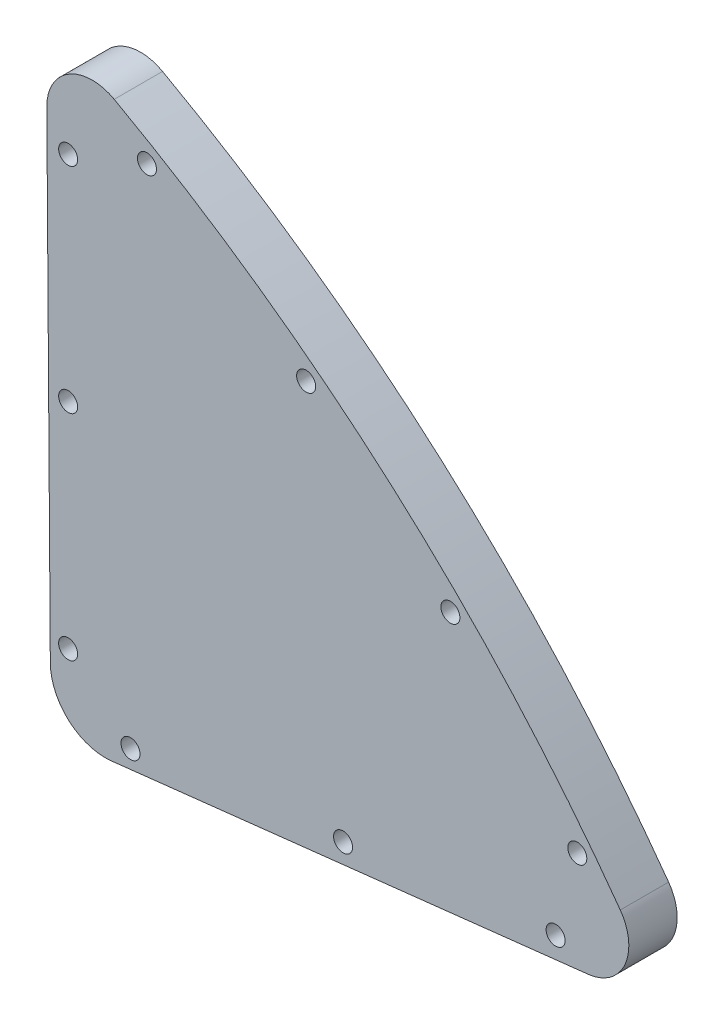
SolidWorks part; units mm, degrees
ref_plane "Front Plane" through (0, 0, 0) normal (0, 0, 1) x (1, 0, 0)
ref_plane "Top Plane" through (0, 0, 0) normal (0, 1, 0) x (1, 0, 0)
ref_plane "Right Plane" through (0, 0, 0) normal (1, 0, 0) x (0, 0, -1)
sketch "Sketch1" plane through (0, 0, 0) normal (0, 0, 1) x (1, 0, 0)
  line L27 (0.9289, -25.6035) -> (126.2631, -11.5065)
  line L28 (-16.0858, 114.7994) -> (-15.167, -11.3217)
  line L29 (0.9289, -25.6035) -> (126.2631, -11.5065)
  line L30 (-16.0858, 114.7994) -> (-15.167, -11.3217)
  arc A47 (-15.167, -11.3217) -> (0.9289, -25.6035) centre (-0.6893, -11.2163) ccw
  arc A48 (126.2631, -11.5065) -> (134.6163, 7.3328) centre (124.9288, 0.3567) ccw
  arc A49 (134.6163, 7.3328) -> (1.6255, 125.3353) centre (-194.5558, -229.707) ccw
  arc A50 (1.6255, 125.3353) -> (-16.0858, 114.7994) centre (-4.1481, 114.8864) ccw
  arc A51 (-15.167, -11.3217) -> (0.9289, -25.6035) centre (-0.6893, -11.2163) ccw
  arc A52 (126.2631, -11.5065) -> (134.6163, 7.3328) centre (124.9288, 0.3567) ccw
  arc A53 (134.6163, 7.3328) -> (1.6255, 125.3353) centre (-194.5558, -229.707) ccw
  arc A54 (1.6255, 125.3353) -> (-16.0858, 114.7994) centre (-4.1481, 114.8864) ccw
  dimension "D1" = 0.762
extrude "Boss-Extrude1" add sketch "Sketch1" along normal blind 12.7
sketch "Sketch2" plane through (0, 0, 0) normal (0, 0, -1) x (-1, 0, 0)
  line L0 (10.2514, 125.1463) -> (3.3584, 113.6037) construction
  line L1 (5.7815, -9.5607) -> (15.1798, -9.5607) construction
  line L2 (16.0858, 114.7994) -> (15.167, -11.3217) construction
  line L3 (10.4807, -9.5607) -> (10.4807, -5.7507) construction
  line L4 (10.4807, -5.7507) -> (10.4807, 50.5103) construction
  line L5 (-74.6657, 73.7101) -> (-71.547, 70.1953) construction
  line L6 (31.0337, -45.4148) -> (-68.4283, 66.6804) construction
  line L7 (10.4807, 106.7713) -> (10.4807, 50.5103) construction
  line L8 (-71.547, 70.1953) -> (-68.4283, 66.6804) construction
  line L9 (-10.2283, 114.9893) -> (-52.0657, 86.4099) construction
  line L10 (-52.0657, 86.4099) -> (-89.9648, 52.7821) construction
  circle A0 centre (10.4807, 106.7713) radius 2.5
  circle A1 centre (10.4807, 50.5103) radius 2.5
  circle A2 centre (10.4807, -5.7507) radius 2.5
  circle A3 centre (-52.0657, 86.4099) radius 2.5
  arc A5 (16.0858, 114.7994) -> (-1.6255, 125.3353) centre (4.1481, 114.8864) ccw construction
  arc A6 (6.6369, 107.8499) -> (-3.2639, 113.6201) centre (0.0331, 107.898) ccw construction
  circle A7 centre (-89.9648, 52.7821) radius 2.5
  arc A8 (-3.2639, 113.6201) -> (-122.7894, 7.5653) centre (194.5558, -229.707) ccw construction
  circle A9 centre (-123.3201, 14.6431) radius 2.5
  circle A10 centre (-10.2283, 114.9893) radius 2.5
  circle A11 centre (-117.6249, -6.8966) radius 2.5
  arc A17 (-89.9648, 52.7821) -> (-52.0657, 86.4099) centre (194.5558, -229.707) cw construction
  arc A18 (-10.2283, 114.9893) -> (-52.0657, 86.4099) centre (194.5558, -229.707) ccw construction
  arc A19 (-1.6255, 125.3353) -> (-134.6163, 7.3328) centre (194.5558, -229.707) ccw construction
  circle A20 centre (-61.7638, -13.5921) radius 2.5
  circle A21 centre (-5.9026, -20.2876) radius 2.5
  point P8 (0, 0)
  point P35 (0, 0)
  point P37 (0, 0)
  dimension "D1" = 5
  dimension "D4" = 22.86
  dimension "D3" = 112.522
  dimension "D2" = 3.81
extrude "Cut-Extrude1" cut sketch "Sketch2" against normal through all
